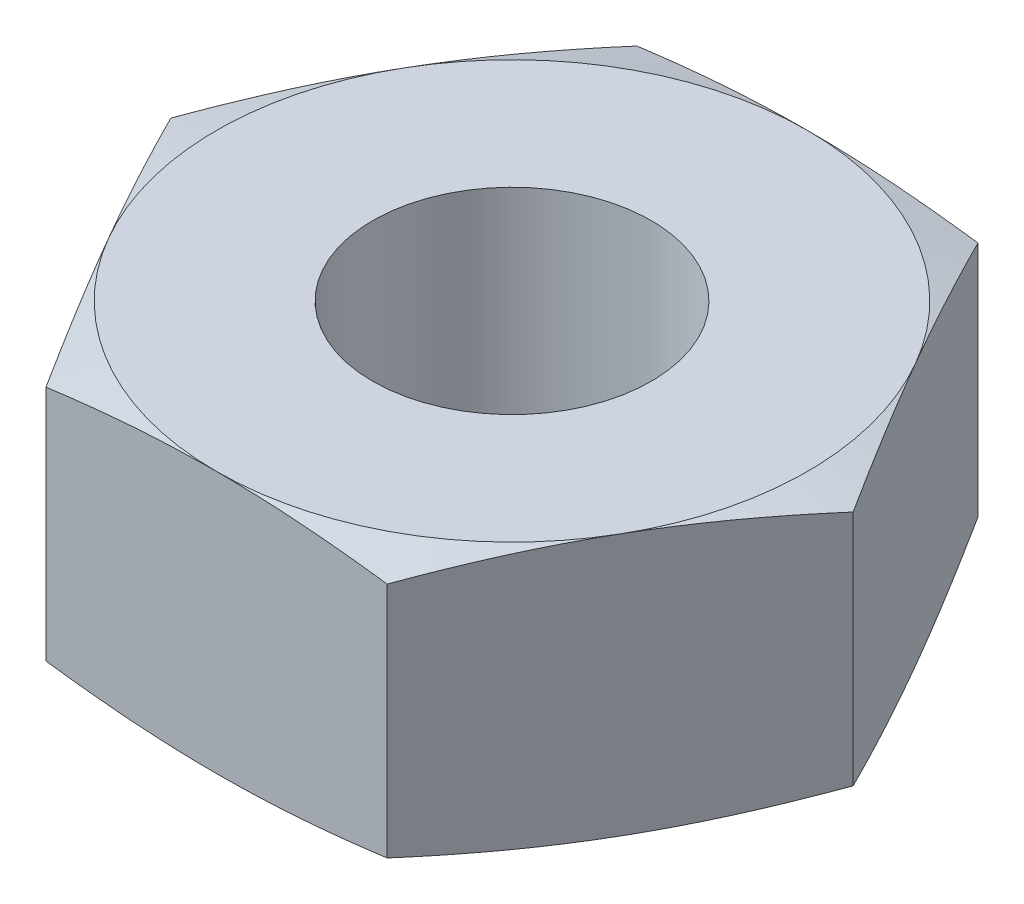
SolidWorks part; units mm, degrees
ref_plane "前视基准面" through (0, 0, 0) normal (0, 0, 1) x (1, 0, 0)
ref_plane "上视基准面" through (0, 0, 0) normal (0, 1, 0) x (1, 0, 0)
ref_plane "右视基准面" through (0, 0, 0) normal (1, 0, 0) x (0, 0, -1)
other "Configuration Table"
sketch "草图1" plane through (0, 0, 0) normal (0, 1, 0) x (1, 0, 0)
  line L1 (4.0415, 0) -> (2.0207, 3.5)
  line L2 (2.0207, 3.5) -> (-2.0207, 3.5)
  line L3 (-2.0207, 3.5) -> (-4.0415, 0)
  line L4 (-4.0415, 0) -> (-2.0207, -3.5)
  line L5 (-2.0207, -3.5) -> (2.0207, -3.5)
  line L6 (2.0207, -3.5) -> (4.0415, 0)
  circle A0 centre (0, 0) radius 3.5 construction
  dimension "D1" = 7
extrude "凸台-拉伸1" add sketch "草图1" along normal blind 3.1
hole_wizard "M4 螺纹孔1" positions "草图2" profile "草图3" tap size "M4" standard "GB" end condition through all
sketch "草图2" plane through (0, 3.1, 0) normal (0, 1, 0) x (1, 0, 0)
  point P0 (0, 0)
sketch "草图3" plane through (0, 3.1, 0) normal (1, 0, 0) x (0, 0, 1)
  line L0 (0, 0) -> (0, 3.1)
  line L1 (0, 3.1) -> (1.65, 3.1)
  line L2 (1.65, 3.1) -> (1.65, 0)
  line L5 (1.65, 0) -> (0, 0)
  line L11 (0, -6.35) -> (0, 107.95) construction
  dimension "通孔螺纹孔钻头直径" = 3.3
  dimension "通孔螺纹孔钻头深度" = 3.1
cosmetic thread "孔螺纹线1" parameters "D2"=4
sketch "草图5" plane through (0, 0, 0) normal (1, 0, 0) x (0, 0, -1)
  line L0 (0, 0) -> (0, -50000) construction
  line L1 (-3.5, 1.55) -> (49996.5, 1.55) construction
  line L2 (-3.5, 3.1) -> (-3.5, 0) construction
  line L3 (-3.5, 0) -> (-4.3871, 0.2377)
  line L4 (-4.3871, 0.2377) -> (-4.3871, -0.8558)
  line L5 (-4.3871, -0.8558) -> (-3.5, 0)
  line L6 (-4.3871, 3.9558) -> (-3.5, 3.1)
  line L7 (-4.3871, 2.8623) -> (-4.3871, 3.9558)
  line L8 (-3.5, 3.1) -> (-4.3871, 2.8623)
  point P7 (-3.5, 1.55)
  dimension "D1" = 75
revolve "切除-旋转1" cut sketch "草图5" angle 360 about L0
